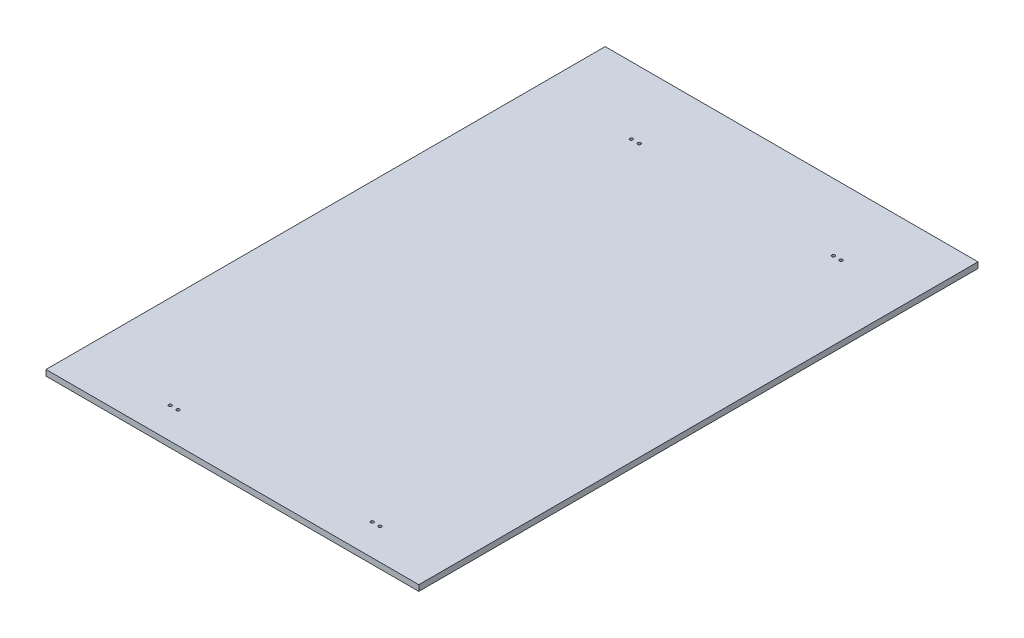
SolidWorks part; units mm, degrees
material "Maple"
ref_plane "Front Plane" through (0, 0, 0) normal (0, 0, 1) x (1, 0, 0)
ref_plane "Top Plane" through (0, 0, 0) normal (0, 1, 0) x (1, 0, 0)
ref_plane "Right Plane" through (0, 0, 0) normal (1, 0, 0) x (0, 0, -1)
sketch "Sketch1" plane through (0, 0, 0) normal (0, 1, 0) x (1, 0, 0)
  line L1 (-609.6, 914.4) -> (609.6, 914.4)
  line L2 (-609.6, 914.4) -> (-609.6, -914.4)
  line L3 (-609.6, -914.4) -> (609.6, -914.4)
  line L4 (609.6, 914.4) -> (609.6, -914.4)
  line L5 (-609.6, 914.4) -> (609.6, -914.4) construction
  line L6 (-609.6, -914.4) -> (609.6, 914.4) construction
  point P0 (0, 0)
  dimension "D1" = 1219.2
  dimension "D2" = 1828.8
extrude "Boss-Extrude1" add sketch "Sketch1" along normal blind 19.05
hole_wizard "3/8 Clearance Hole1" positions "Sketch3" profile "Sketch2" hole size "3/8" standard "ANSI Inch" end condition up to next
sketch "Sketch3" plane through (0, 19.05, 0) normal (0, 1, 0) x (1, 0, 0)
  line L1 (-304.8, 695.2996) -> (381, 695.2996) construction
  line L2 (-304.8, 695.2996) -> (-304.8, -812.8) construction
  line L3 (-304.8, -812.8) -> (381, -812.8) construction
  line L4 (381, 695.2996) -> (381, -812.8) construction
  line L5 (-279.4, 695.2996) -> (-279.4, -812.8) construction
  line L7 (355.6, 695.2996) -> (355.6, -812.8) construction
  line L9 (-609.6, -914.4) -> (609.6, -914.4) construction
  line L10 (609.6, -914.4) -> (609.6, 914.4) construction
  point P1 (-304.8, 695.2996)
  point P2 (381, -812.8)
  point P311 (-304.8, -812.8)
  point P312 (381, 695.2996)
  point P320 (355.6, -812.8)
  point P324 (-279.4, -812.8)
  point P326 (-279.4, 695.2996)
  point P328 (355.6, 695.2996)
  dimension "D1" = 25.4
  dimension "D2" = 25.4
  dimension "D3" = 1508.0996
  dimension "D4" = 101.6
  dimension "D5" = 685.8
  dimension "D6" = 228.6
sketch "Sketch2" plane through (-304.8, 19.05, -695.2996) normal (1, 0, 0) x (0, 0, 1)
  line L0 (0, 0) -> (0, 19.05)
  line L1 (0, 19.05) -> (5.0419, 19.05)
  line L2 (5.0419, 19.05) -> (5.0419, 0)
  line L5 (5.0419, 0) -> (0, 0)
  line L11 (0, -6.35) -> (0, 107.95) construction
  dimension "Thru Hole Dia." = 10.0838
  dimension "Thru Hole Depth" = 19.05
